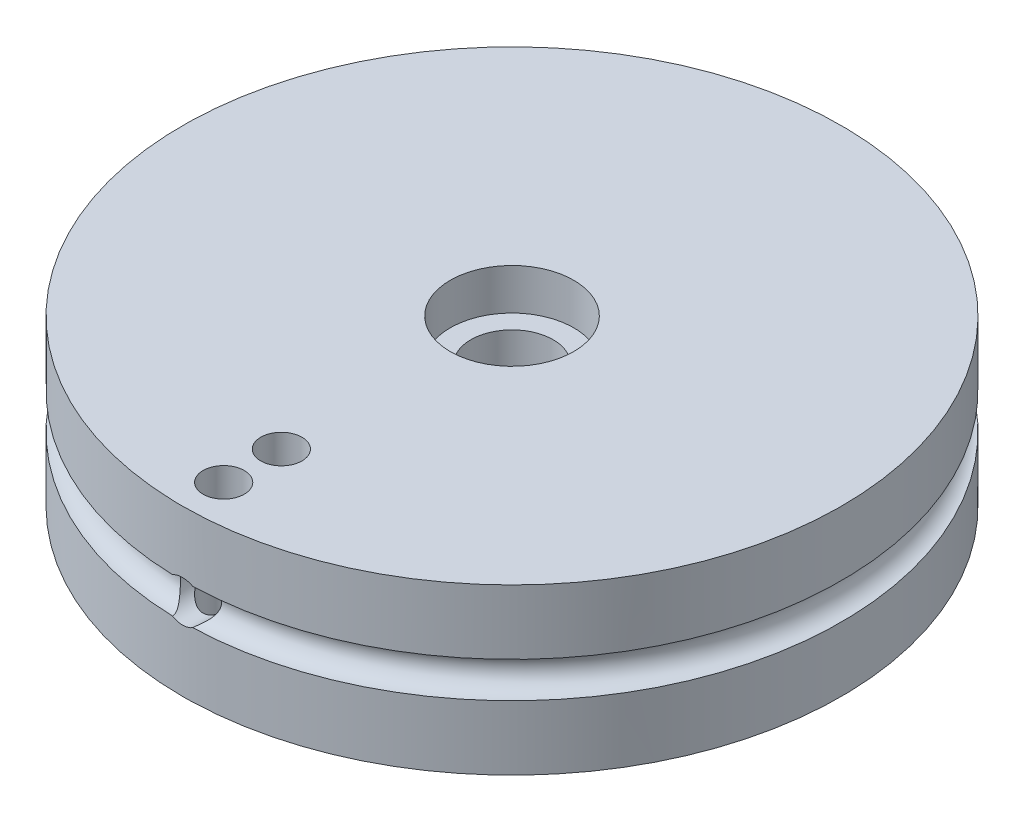
SolidWorks part; units mm, degrees
ref_plane "Front Plane" through (0, 0, 0) normal (0, 0, 1) x (1, 0, 0)
ref_plane "Top Plane" through (0, 0, 0) normal (0, 1, 0) x (1, 0, 0)
ref_plane "Right Plane" through (0, 0, 0) normal (1, 0, 0) x (0, 0, -1)
sketch "Sketch1" plane through (0, 0, 0) normal (0, 1, 0) x (1, 0, 0)
  circle A0 centre (0, 0) radius 2.3813
  circle A1 centre (0, 0) radius 10.16
  dimension "D1" = 4.7625
  dimension "D2" = 20.32
extrude "Boss-Extrude1" add sketch "Sketch1" along normal blind 5.08
sketch "Sketch2" plane through (0, 5.08, 0) normal (0, 1, 0) x (1, 0, 0)
  circle A0 centre (0, 0) radius 2.3813
  circle A1 centre (0, 0) radius 1.27
  point P4 (0, 0)
  dimension "D1" = 2.54
extrude "Boss-Extrude2" add sketch "Sketch2" against normal blind 2.54
sketch "Sketch3" plane through (0, 5.08, 0) normal (0, 1, 0) x (1, 0, 0)
  circle A0 centre (0, 0) radius 1.905
  dimension "D1" = 3.81
extrude "Cut-Extrude1" cut sketch "Sketch3" against normal blind 1.27
sketch "Sketch4" plane through (0, 0, 0) normal (0, 0, 1) x (1, 0, 0)
  line L0 (10.16, 0) -> (10.16, 5.08) construction
  line L1 (0, 6.4745) -> (0, -4.0103) construction
  circle A0 centre (10.16, 2.54) radius 0.5521
revolve "Cut-Revolve1" cut sketch "Sketch4" angle 360 about L1
sketch "Sketch5" plane through (0, 5.08, 0) normal (0, 1, 0) x (1, 0, 0)
  line L0 (0, -10.16) -> (-13.4798, -10.16) construction
  circle A0 centre (0, -8.89) radius 0.635
  circle A1 centre (0, -7.112) radius 0.635
  circle A2 centre (0, 0) radius 10.16 construction
  dimension "D1" = 1.27
  dimension "D2" = 1.778
extrude "Cut-Extrude2" cut sketch "Sketch5" against normal through all
ref_plane "Plane1" through (0, 0, 10.16) normal (0, 0, 1) x (1, 0, 0)
sketch "Sketch6" plane through (0, 0, 10.16) normal (0, 0, 1) x (1, 0, 0)
  line L0 (0, 0) -> (0, 5.08) construction
  line L1 (0.635, 5.08) -> (-0.635, 5.08) construction
  line L2 (0, 5.08) -> (0, 2.54) construction
  line L3 (0, 2.54) -> (8.0366, 2.54) construction
  circle A0 centre (0, 2.54) radius 0.635
extrude "Cut-Extrude3" cut sketch "Sketch6" against normal blind 3.683
